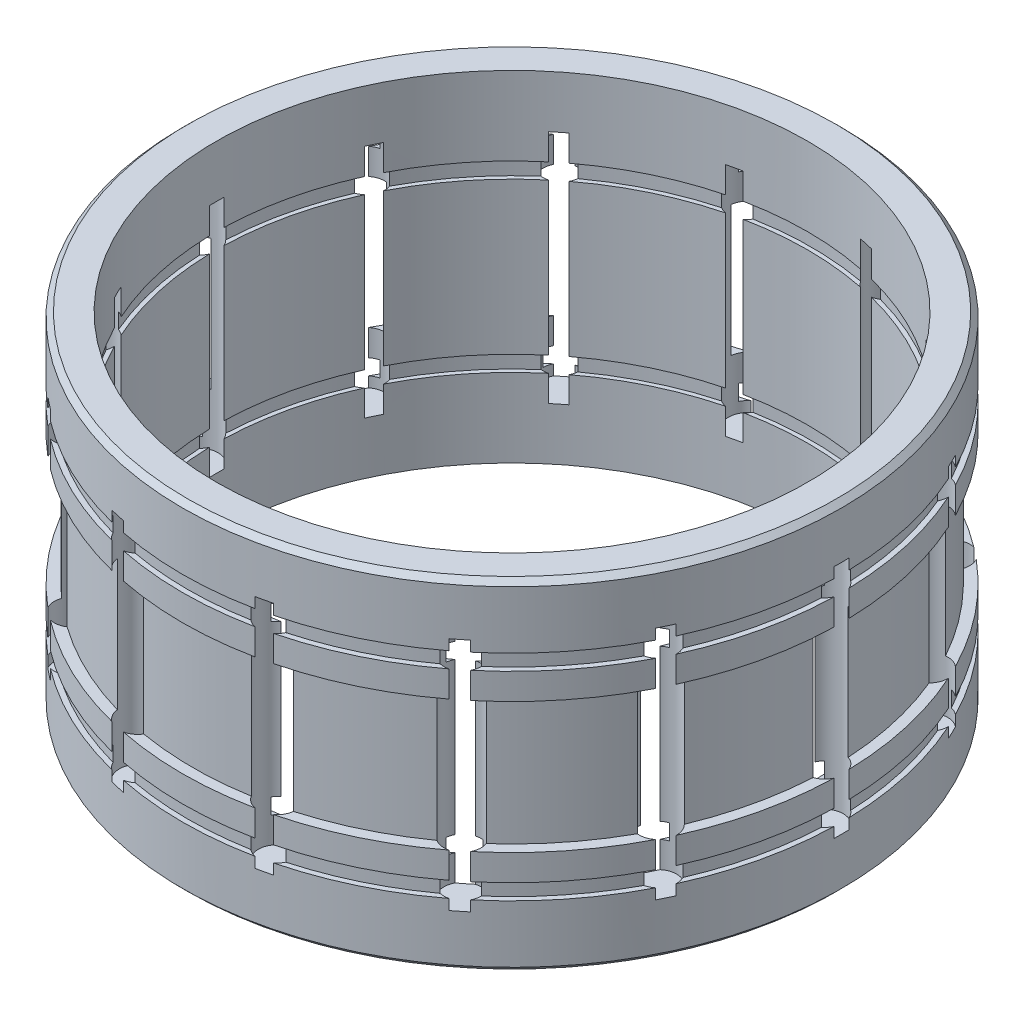
SolidWorks part; units mm, degrees
material "AISI 316 Annealed Stainless Steel Bar (SS)"
ref_plane "Front Plane" through (0, 0, 0) normal (0, 0, 1) x (1, 0, 0)
ref_plane "Top Plane" through (0, 0, 0) normal (0, 1, 0) x (1, 0, 0)
ref_plane "Right Plane" through (0, 0, 0) normal (1, 0, 0) x (0, 0, -1)
sketch "Sketch1" plane through (0, 0, 0) normal (0, 0, 1) x (1, 0, 0)
  line L0 (0, 0) -> (0, 92.5599) construction
  line L1 (0, 0) -> (16.002, 0) construction
  line L2 (16.002, 16.51) -> (16.002, 13.462)
  line L3 (16.002, 16.51) -> (0, 16.51) construction
  line L17 (16.002, 0) -> (14.351, 0)
  line L18 (14.351, 0) -> (14.351, 3.81)
  line L19 (14.351, 3.81) -> (14.5542, 3.81)
  line L20 (14.5542, 3.81) -> (14.5542, 4.572)
  line L21 (14.5542, 4.572) -> (14.351, 4.572)
  line L22 (14.351, 4.572) -> (14.351, 11.938)
  line L23 (14.351, 11.938) -> (14.5542, 11.938)
  line L24 (14.5542, 11.938) -> (14.5542, 12.7)
  line L25 (14.5542, 12.7) -> (14.351, 12.7)
  line L26 (14.351, 12.7) -> (14.351, 16.51)
  line L27 (14.351, 12.7) -> (14.351, 11.938) construction
  line L28 (14.351, 4.572) -> (14.351, 3.81) construction
  line L29 (14.351, 16.51) -> (16.002, 16.51)
  line L30 (16.002, 13.462) -> (15.748, 13.462)
  line L31 (15.748, 13.462) -> (15.748, 12.7)
  line L32 (15.748, 12.7) -> (16.002, 12.7)
  line L33 (16.002, 12.7) -> (16.002, 11.43)
  line L34 (16.002, 11.43) -> (15.494, 11.43)
  line L35 (15.494, 11.43) -> (15.494, 5.08)
  line L36 (15.494, 5.08) -> (16.002, 5.08)
  line L37 (16.002, 5.08) -> (16.002, 3.81)
  line L38 (16.002, 3.81) -> (15.748, 3.81)
  line L39 (15.748, 3.81) -> (15.748, 3.048)
  line L40 (15.748, 3.048) -> (16.002, 3.048)
  line L41 (16.002, 3.048) -> (16.002, 0)
  dimension "D1" = 92.5599
  dimension "D2" = 16.002
  dimension "D3" = 1.651
  dimension "D4" = 0.2032
  dimension "D5" = 3.81
  dimension "D6" = 0.762
  dimension "D7" = 0.254
  dimension "D8" = 0.508
  dimension "D9" = 5.08
  dimension "D10" = 16.51
revolve "Revolve1" add sketch "Sketch1" angle 360 about L0
sketch "Sketch2" plane through (0, 0, 0) normal (0, 0, 1) x (1, 0, 0)
  line L0 (16.002, 16.51) -> (-16.002, 16.51) construction
  line L5 (15.1765, 16.51) -> (15.1765, 13.97) construction
  line L6 (14.351, 16.51) -> (-14.351, 16.51) construction
  line L7 (15.1765, 2.54) -> (15.1765, 0) construction
  line L8 (16.002, 16.51) -> (-16.002, 16.51) construction
  line L10 (14.351, 16.51) -> (-14.351, 16.51) construction
  line L11 (16.002, 16.51) -> (14.351, 16.51) construction
  line L12 (15.1765, 16.51) -> (15.1765, 0) construction
  line L13 (-16.002, 0) -> (16.002, 0) construction
  line L15 (15.1765, 13.97) -> (16.0782, 13.97)
  line L16 (15.1765, 13.97) -> (15.1765, 2.54)
  line L17 (15.1765, 2.54) -> (16.0782, 2.54)
  line L18 (16.0782, 13.97) -> (16.0782, 2.54)
  dimension "D1" = 0.9017
  dimension "D2" = 11.43
revolve "Cut-Revolve1" cut sketch "Sketch2" angle 360 about L16
pattern_circular "CirPattern1" count 14 over 360 about axis through (0, 0, 0) along (0, 1, 0) of "Cut-Revolve1"
chamfer "Chamfer1" distance 0.254 angle 45 2 edges at (0, 16.51, -16.002) (0, 0, -16.002)
ref_plane "Plane1" through (0, 8.255, 0) normal (0, 1, 0) x (1, 0, 0)
